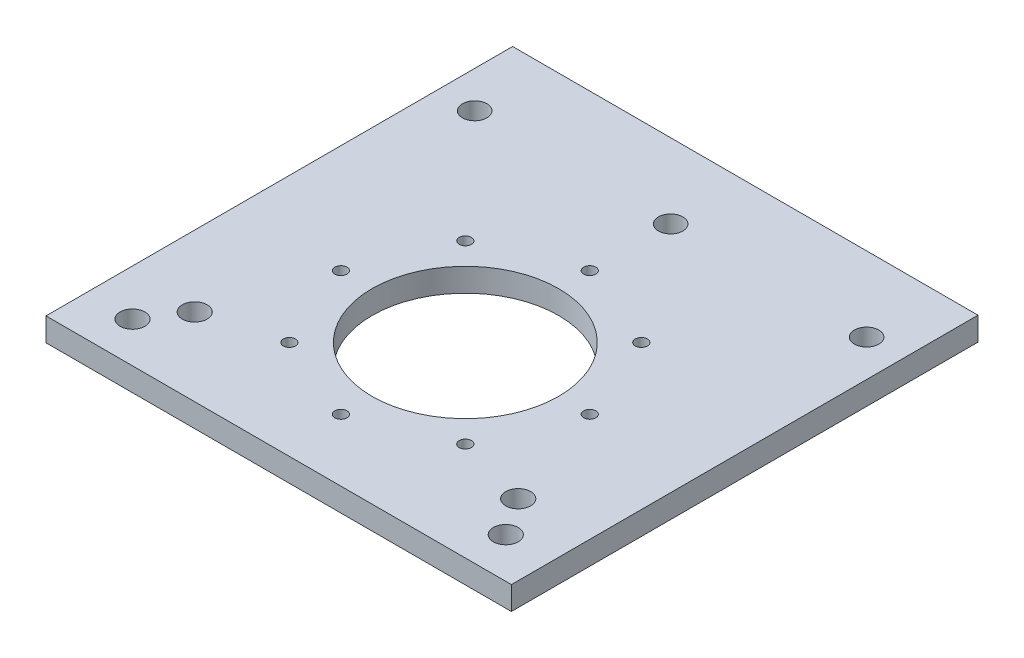
SolidWorks part; units mm, degrees
material "6061 Alloy"
ref_plane "Front Plane" through (0, 0, 0) normal (0, 0, 1) x (1, 0, 0)
ref_plane "Top Plane" through (0, 0, 0) normal (0, 1, 0) x (1, 0, 0)
ref_plane "Right Plane" through (0, 0, 0) normal (1, 0, 0) x (0, 0, -1)
sketch "Sketch2" plane through (0, 0, 0) normal (0, 1, 0) x (1, 0, 0)
  line L0 (0, 0) -> (0, 34.925) construction
  line L1 (-47.5, -60.325) -> (-47.5, 34.925)
  line L2 (47.5, -60.325) -> (47.5, 34.925)
  line L3 (-47.5, 34.925) -> (47.5, 34.925)
  line L4 (-47.5, -60.325) -> (47.5, -60.325)
  point P3 (47.5, -12.7)
  point P5 (0, 34.925)
  point P12 (0, -60.325)
  dimension "D1" = 95.25
  dimension "D2" = 95
  dimension "D3" = 12.7
extrude "Boss-Extrude3" add sketch "Sketch2" along normal blind 4.7625
sketch "Sketch3" plane through (0, 4.7625, 0) normal (0, 1, 0) x (1, 0, 0)
  line L0 (47.5, 34.925) -> (-47.5, 34.925) construction
  circle A1 centre (0, -22.225) radius 19.05
  dimension "D2" = 38.1
  dimension "D3" = 57.15
extrude "Cut-Extrude1" cut sketch "Sketch3" against normal through all
sketch "Sketch4" plane through (0, 4.7625, 0) normal (0, 1, 0) x (1, 0, 0)
  line L0 (47.5, 34.925) -> (-47.5, 34.925) construction
  line L1 (0, 34.925) -> (0, 55.3884) construction
  point P0 (-40, 19.685)
  point P7 (40, 19.685)
  point P8 (0, 19.685)
  point P10 (0, 19.685)
  dimension "D1" = 15.24
  dimension "D2" = 80
hole_wizard "M6x1.0 Tapped Hole1" positions "Sketch4" profile "Sketch6" tap size "M6x1.0" standard "ANSI Metric"
sketch "Sketch6" plane through (-40, 4.7625, -19.685) normal (1, 0, 0) x (0, 0, 1)
  line L0 (0, 0) -> (0, 6.2647)
  line L1 (0, 6.2647) -> (2.5, 4.7625)
  line L2 (2.5, 4.7625) -> (2.5, 0)
  line L5 (2.5, 0) -> (0, 0)
  line L10 (0, 6.2647) -> (-2.5, 4.7625) construction
  line L11 (0, -6.35) -> (0, 107.95) construction
  dimension "Tap Drill Dia." = 5
  dimension "Tap Drill Depth" = 4.7625
  dimension "Drill Angle" = 118
sketch "Sketch7" plane through (0, 4.7625, 0) normal (0, 1, 0) x (1, 0, 0)
  line L0 (0, 0) -> (0, -60.325) construction
  line L1 (-47.5, -60.325) -> (47.5, -60.325) construction
  circle A0 centre (-33.02, -44.45) radius 2.54
  circle A1 centre (33.02, -44.45) radius 2.54
  circle A2 centre (-38.1, -52.07) radius 2.54
  circle A3 centre (38.1, -52.07) radius 2.54
  dimension "D3" = 5.08
  dimension "D4" = 5.08
  dimension "D6" = 38.1
  dimension "D1" = 44.45
  dimension "D2" = 33.02
  dimension "D5" = 7.62
extrude "Cut-Extrude2" cut sketch "Sketch7" against normal blind 7.62
sketch "Sketch12" plane through (0, 4.7625, 0) normal (0, 1, 0) x (1, 0, 0)
  line L0 (47.5, 34.925) -> (-47.5, 34.925) construction
  circle A0 centre (0, -22.225) radius 25.4
  circle A1 centre (0, 3.175) radius 1.2446
  circle A2 centre (17.9605, -4.2645) radius 1.2446
  circle A3 centre (25.4, -22.225) radius 1.2446
  circle A4 centre (17.9605, -40.1855) radius 1.2446
  circle A5 centre (0, -47.625) radius 1.2446
  circle A6 centre (-17.9605, -40.1855) radius 1.2446
  circle A7 centre (-25.4, -22.225) radius 1.2446
  circle A8 centre (-17.9605, -4.2645) radius 1.2446
  point P4 (1.599, -21.368)
  point P13 (0, 0)
  point P25 (0, -22.225)
  dimension "D1" = 2.4892
  dimension "D2" = 50.8
  dimension "D3" = 57.15
  dimension "D4" = 8
extrude "Cut-Extrude3" cut sketch "Sketch12" against normal through all contours A8 | A7 | A6 | A5 | A4 | A3 | A2 | A1
